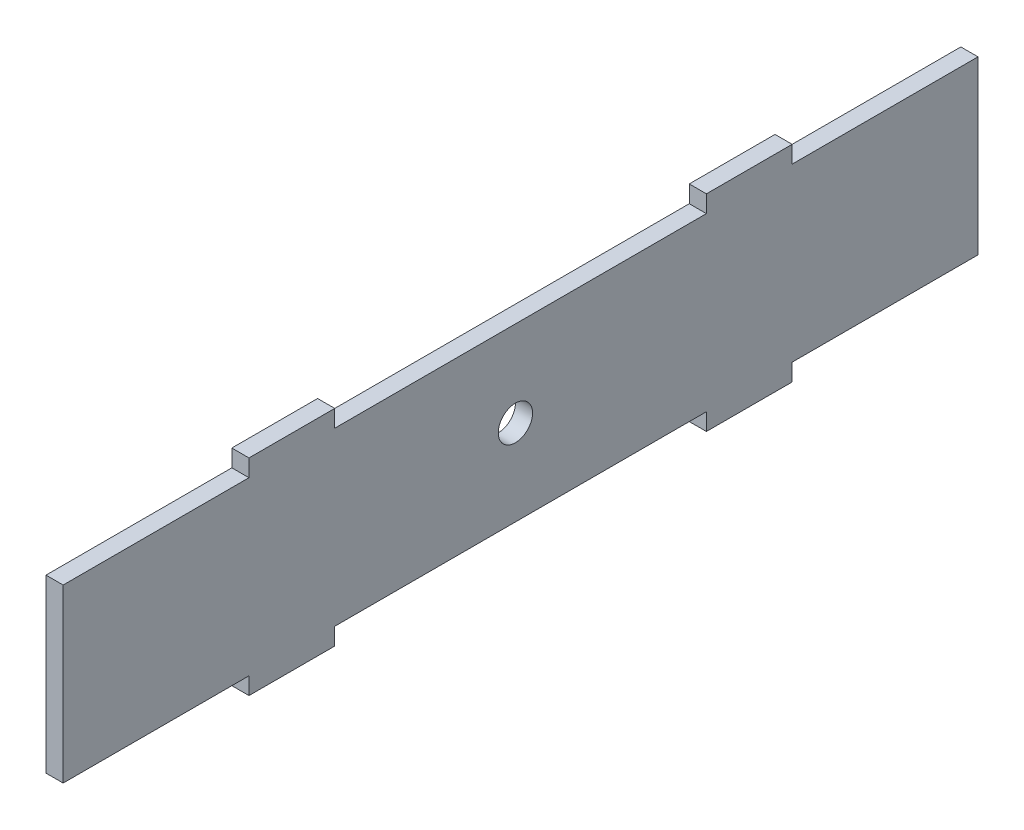
SolidWorks part; units mm, degrees
ref_plane "Front Plane" through (0, 0, 0) normal (0, 0, 1) x (1, 0, 0)
ref_plane "Top Plane" through (0, 0, 0) normal (0, 1, 0) x (1, 0, 0)
ref_plane "Right Plane" through (0, 0, 0) normal (1, 0, 0) x (0, 0, -1)
sketch "Sketch1" plane through (0, 0, 0) normal (1, 0, 0) x (0, 0, -1)
  line L0 (80, 0) -> (80, -57.5619) construction
  line L5 (0, 0) -> (32.5, 0)
  line L6 (0, 0) -> (0, -30)
  line L12 (0, -30) -> (32.5, -30)
  line L17 (160, 0) -> (160, -30)
  line L26 (0, -15) -> (158.1928, -15) construction
  line L27 (0, -30) -> (0, -47.9911) construction
  line L29 (32.5, -30) -> (32.5, -33)
  line L30 (32.5, -33) -> (47.5, -33)
  line L31 (47.5, -30) -> (47.5, -33)
  line L32 (47.5, -30) -> (112.5, -30)
  line L33 (112.5, -30) -> (112.5, -33)
  line L34 (127.5, -33) -> (112.5, -33)
  line L35 (127.5, -30) -> (127.5, -33)
  line L36 (127.5, -30) -> (160, -30)
  line L37 (127.5, 0) -> (127.5, 3)
  line L38 (127.5, 3) -> (112.5, 3)
  line L39 (112.5, 0) -> (112.5, 3)
  line L40 (32.5, 3) -> (47.5, 3)
  line L41 (32.5, 0) -> (32.5, 3)
  line L43 (127.5, 0) -> (160, 0)
  line L44 (47.5, 0) -> (47.5, 3)
  line L45 (47.5, 0) -> (112.5, 0)
  circle A0 centre (79.0964, -15) radius 3
  point P22 (47.5, 0)
  dimension "D6" = 6
  dimension "D1" = 160
  dimension "D2" = 30
  dimension "D3" = 15
  dimension "D4" = 3
  dimension "D5" = 32.5
extrude "Boss-Extrude2" add sketch "Sketch1" along normal blind 3
